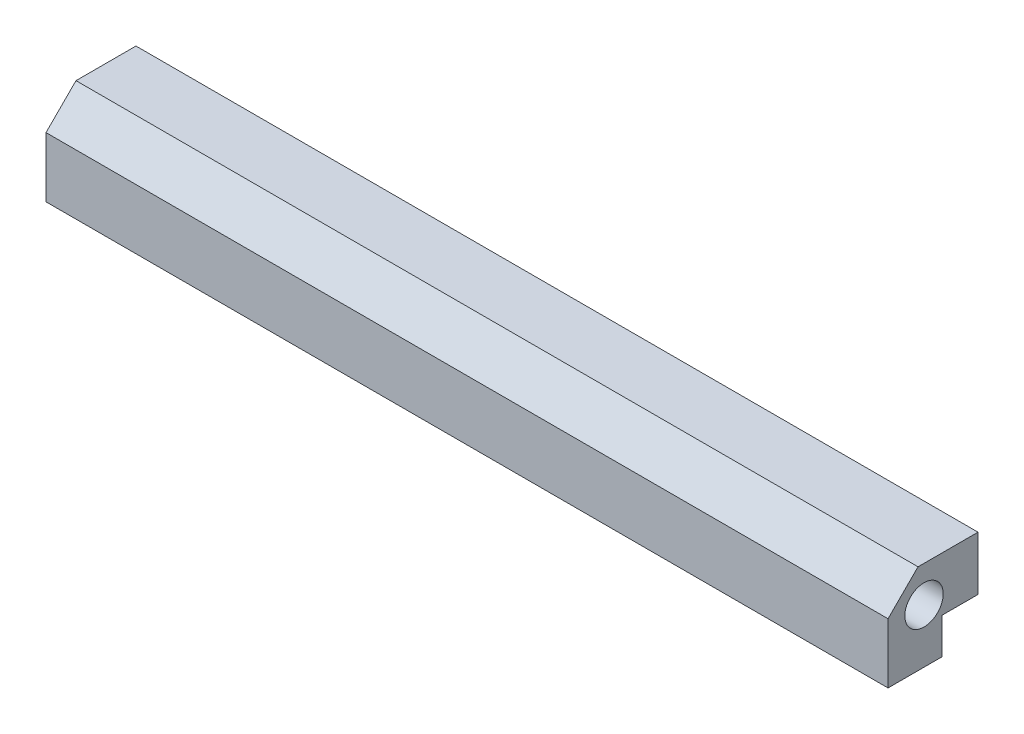
SolidWorks part; units mm, degrees
ref_plane "Plan de face" through (0, 0, 0) normal (0, 0, 1) x (1, 0, 0)
ref_plane "Plan de dessus" through (0, 0, 0) normal (0, 1, 0) x (1, 0, 0)
ref_plane "Plan de droite" through (0, 0, 0) normal (1, 0, 0) x (0, 0, -1)
sketch "Esquisse3" plane through (0, 0, 0) normal (1, 0, 0) x (0, 0, -1)
  line L0 (-4.5, -10.5) -> (-4.5, 4.5)
  line L1 (-4.5, 4.5) -> (10.5, 4.5)
  line L2 (10.5, 4.5) -> (10.5, -4.5)
  line L3 (10.5, -4.5) -> (4.5, -4.5)
  line L4 (4.5, -4.5) -> (4.5, -10.5)
  line L5 (4.5, -10.5) -> (-4.5, -10.5)
  line L6 (-4.5, 4.5) -> (4.5, -4.5) construction
  circle A1 centre (1.5, -1.5) radius 2.35
  point P8 (0, 0)
  dimension "D4" = 4.7
  dimension "D5" = 6
  dimension "D6" = 6
  dimension "D1" = 9
  dimension "D2" = 9
  dimension "D3" = 15
extrude "Boss.-Extru.2" add sketch "Esquisse3" along normal mid plane 140.4
chamfer "Chanfrein1" distance 5 angle 45 1 edges at (0, 4.5, 4.5)
sketch "Esquisse6" plane through (-70.2, 0, 0) normal (-1, 0, 0) x (0, 0, 1)
  circle A0 centre (-1.5, -1.5) radius 2.35 construction
  circle A1 centre (-1.5, -1.5) radius 2.35
  circle A2 centre (-1.5, -1.5) radius 3.2
  dimension "D1" = 6.4
extrude "Enlèv. mat.-Extru.1" cut sketch "Esquisse6" against normal blind 7
sketch "Esquisse7" plane through (70.2, 0, 0) normal (1, 0, 0) x (0, 0, -1)
  circle A0 centre (1.5, -1.5) radius 2.35 construction
  circle A1 centre (1.5, -1.5) radius 2.35
  circle A2 centre (1.5, -1.5) radius 3.2
  dimension "D1" = 6.4
extrude "Enlèv. mat.-Extru.2" cut sketch "Esquisse7" against normal blind 7
